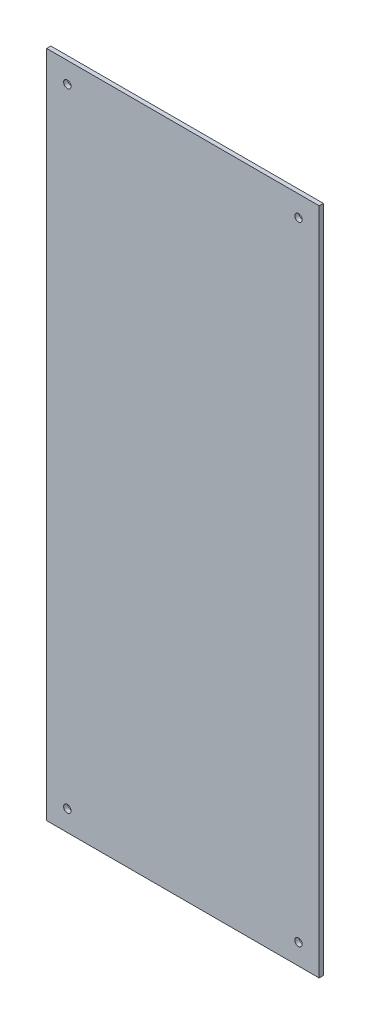
SolidWorks part; units mm, degrees
ref_plane "Front Plane" through (0, 0, 0) normal (1, 0, 0) x (0, 1, 0)
ref_plane "Top Plane" through (0, 0, 0) normal (0, 0, 1) x (0, 1, 0)
ref_plane "Right Plane" through (0, 0, 0) normal (0, 1, 0) x (-1, 0, 0)
sketch "Sketch1" plane through (0, 0, 0) normal (0, 0, 1) x (0, 1, 0)
  line L1 (-250, -100) -> (250, -100)
  line L2 (-250, -100) -> (-250, 100)
  line L3 (-250, 100) -> (250, 100)
  line L4 (250, -100) -> (250, 100)
  line L5 (-250, -100) -> (250, 100) construction
  line L6 (-250, 100) -> (250, -100) construction
  line L7 (237.5, -87.5) -> (-237.5, -87.5) construction
  line L8 (237.5, -87.5) -> (237.5, 87.5) construction
  line L9 (237.5, 87.5) -> (-237.5, 87.5) construction
  line L10 (-237.5, -87.5) -> (-237.5, 87.5) construction
  line L11 (237.5, -87.5) -> (-237.5, 87.5) construction
  line L12 (237.5, 87.5) -> (-237.5, -87.5) construction
  circle A0 centre (-237.5, 87.5) radius 2.8
  circle A1 centre (237.5, 87.5) radius 2.8
  circle A2 centre (237.5, -87.5) radius 2.8
  circle A3 centre (-237.5, -87.5) radius 2.8
  point P0 (0, 0)
  point P6 (0, 0)
  dimension "D3" = 5.6
  dimension "D1" = 200
  dimension "D2" = 500
  dimension "D4" = 12.5
  dimension "D5" = 12.5
extrude "Boss-Extrude1" add sketch "Sketch1" along normal blind 3.175
sketch "Sketch2" plane through (0, 0, 3.175) normal (0, 0, 1) x (1, 0, 0)
  line L1 (-103.175, -253.175) -> (103.175, -253.175)
  line L2 (-103.175, -253.175) -> (-103.175, 253.175)
  line L3 (-103.175, 253.175) -> (103.175, 253.175)
  line L4 (103.175, -253.175) -> (103.175, 253.175)
  line L5 (-103.175, -253.175) -> (103.175, 253.175) construction
  line L6 (-103.175, 253.175) -> (103.175, -253.175) construction
  line L7 (-100, -250) -> (100, -250)
  line L8 (-100, -250) -> (-100, 250)
  line L9 (-100, 250) -> (100, 250)
  line L10 (100, -250) -> (100, 250)
  line L11 (-100, -250) -> (100, 250) construction
  line L12 (-100, 250) -> (100, -250) construction
  point P0 (0, 0)
  point P6 (0, 0)
  dimension "D1" = 3.175
  dimension "D2" = 3.175
extrude "Boss-Extrude2" add sketch "Sketch2" against normal through all
